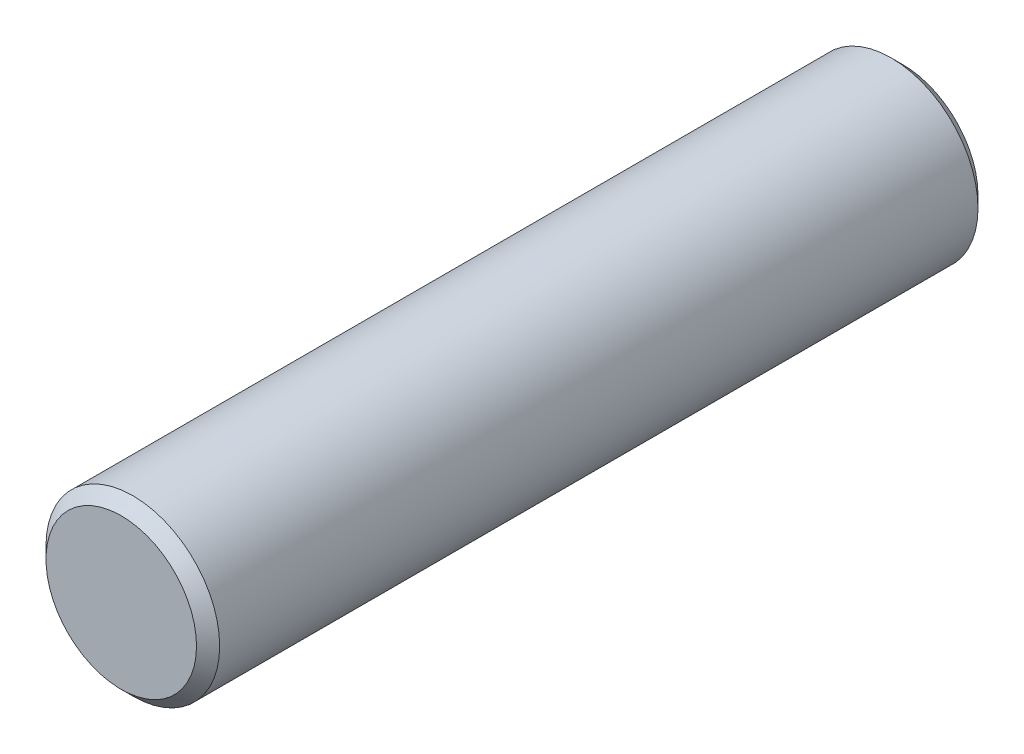
SolidWorks part; units mm, degrees
ref_plane "Front Plane" through (0, 0, 0) normal (0, 0, 1) x (1, 0, 0)
ref_plane "Top Plane" through (0, 0, 0) normal (0, 1, 0) x (1, 0, 0)
ref_plane "Right Plane" through (0, 0, 0) normal (1, 0, 0) x (0, 0, -1)
sketch "Sketch1" plane through (0, 0, 0) normal (0, 0, 1) x (1, 0, 0)
  circle A0 centre (0, 0) radius 1.5
  dimension "D1" = 3
extrude "Boss-Extrude1" add sketch "Sketch1" along normal mid plane 13.5
chamfer "Chamfer1" distance 0.2 angle 45 1 edges at (1.5, 0, 6.75)
chamfer "Chamfer2" distance 0.2 angle 45 1 edges at (1.5, 0, -6.75)
